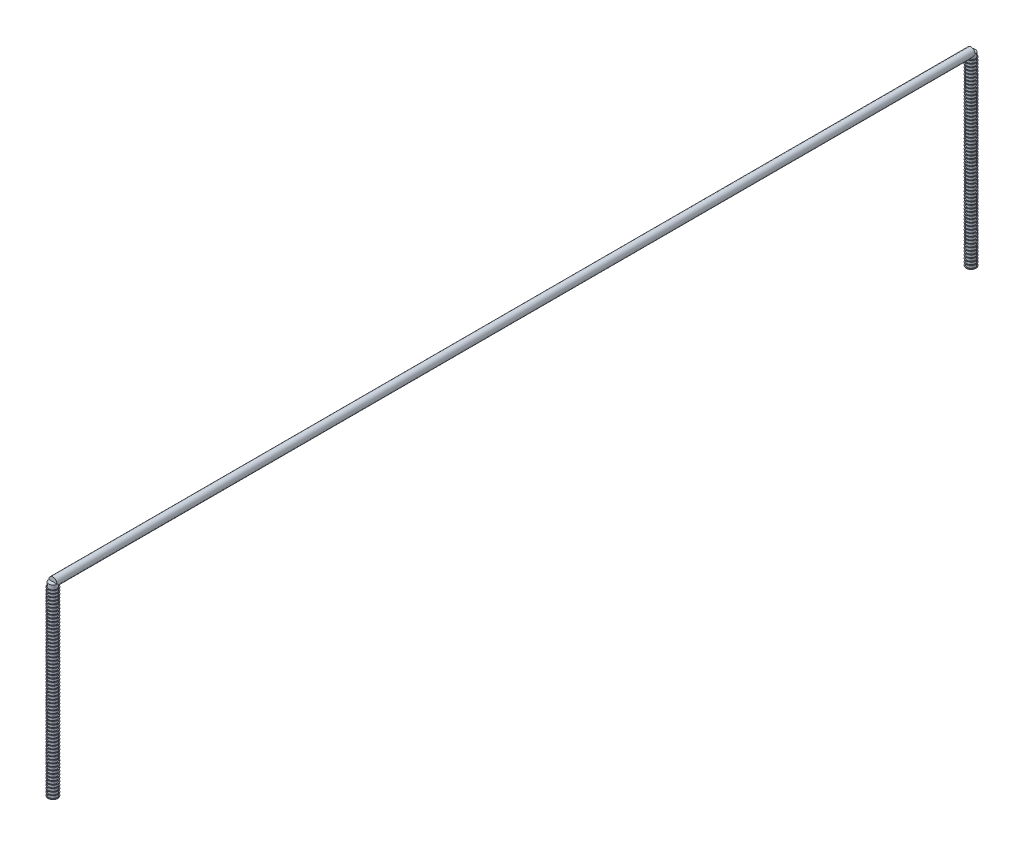
SolidWorks part; units mm, degrees
ref_plane "Alzado" through (0, 0, 0) normal (0, 0, 1) x (1, 0, 0)
ref_plane "Planta" through (0, 0, 0) normal (0, 1, 0) x (1, 0, 0)
ref_plane "Vista lateral" through (0, 0, 0) normal (1, 0, 0) x (0, 0, -1)
sketch "Croquis1" plane through (0, 0, 0) normal (0, 0, 1) x (1, 0, 0)
  circle A0 centre (0, 0) radius 40
  dimension "D1" = 80
extrude "Saliente-Extruir1" add sketch "Croquis1" along normal blind 9000
sketch "Croquis2" plane through (0, 0, 0) normal (0, 1, 0) x (1, 0, 0)
  line L0 (-40, -9000) -> (40, -9000) construction
  circle A0 centre (0, 0) radius 40
  circle A1 centre (0, -9000) radius 40
extrude "Saliente-Extruir2" add sketch "Croquis2" against normal blind 1816
sketch "Croquis3" plane through (0, -1816, 0) normal (0, -1, 0) x (1, 0, 0)
  circle A0 centre (0, 9000) radius 47.8249
extrude "Saliente-Extruir3" add sketch "Croquis3" against normal blind 5
pattern_linear "MatrizL1" count 60 spacing 30 along (0, 1, 0) of "Saliente-Extruir3"
pattern_linear "MatrizL2" count 2 spacing 9000 along (0, 0, -1) of "MatrizL1", "Saliente-Extruir3"
